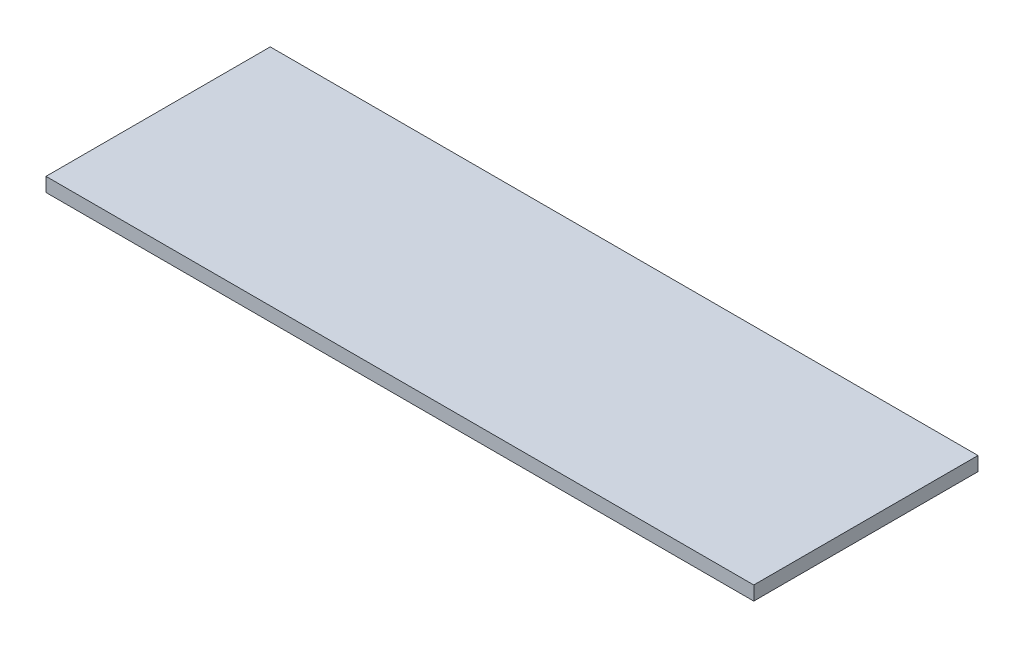
SolidWorks part; units mm, degrees
material "Maple"
ref_plane "Front Plane" through (0, 0, 0) normal (0, 0, 1) x (1, 0, 0)
ref_plane "Top Plane" through (0, 0, 0) normal (0, 1, 0) x (1, 0, 0)
ref_plane "Right Plane" through (0, 0, 0) normal (1, 0, 0) x (0, 0, -1)
sketch "Sketch1" plane through (0, 0, 0) normal (0, 1, 0) x (1, 0, 0)
  line L1 (0, 0) -> (641.35, 0)
  line L2 (0, 0) -> (0, 203.2)
  line L3 (0, 203.2) -> (641.35, 203.2)
  line L4 (641.35, 0) -> (641.35, 203.2)
  dimension "D1" = 641.35
  dimension "D2" = 203.2
extrude "Boss-Extrude1" add sketch "Sketch1" along normal blind 12.7
